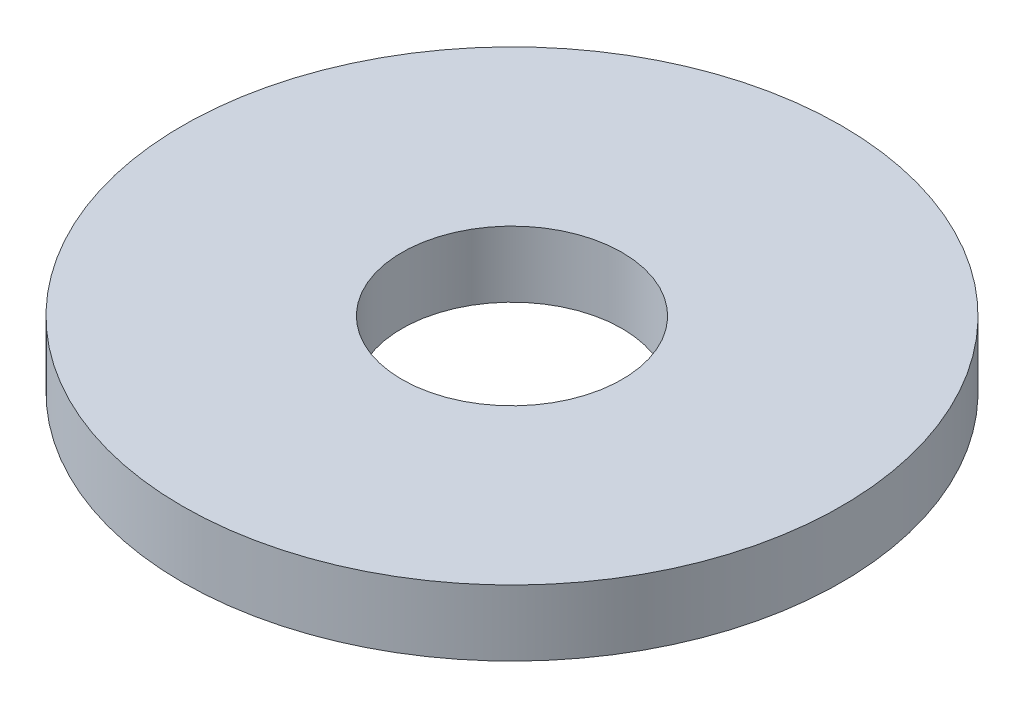
SolidWorks part; units mm, degrees
ref_plane "Front Plane" through (0, 0, 0) normal (0, 0, 1) x (1, 0, 0)
ref_plane "Top Plane" through (0, 0, 0) normal (0, 1, 0) x (1, 0, 0)
ref_plane "Right Plane" through (0, 0, 0) normal (1, 0, 0) x (0, 0, -1)
sketch "Sketch1" plane through (0, 0, 0) normal (0, 1, 0) x (1, 0, 0)
  circle A0 centre (0, 0) radius 8.35
  circle A1 centre (0, 0) radius 25
  dimension "D1" = 50
  dimension "D2" = 16.7
extrude "Boss-Extrude1" add sketch "Sketch1" along normal blind 5
